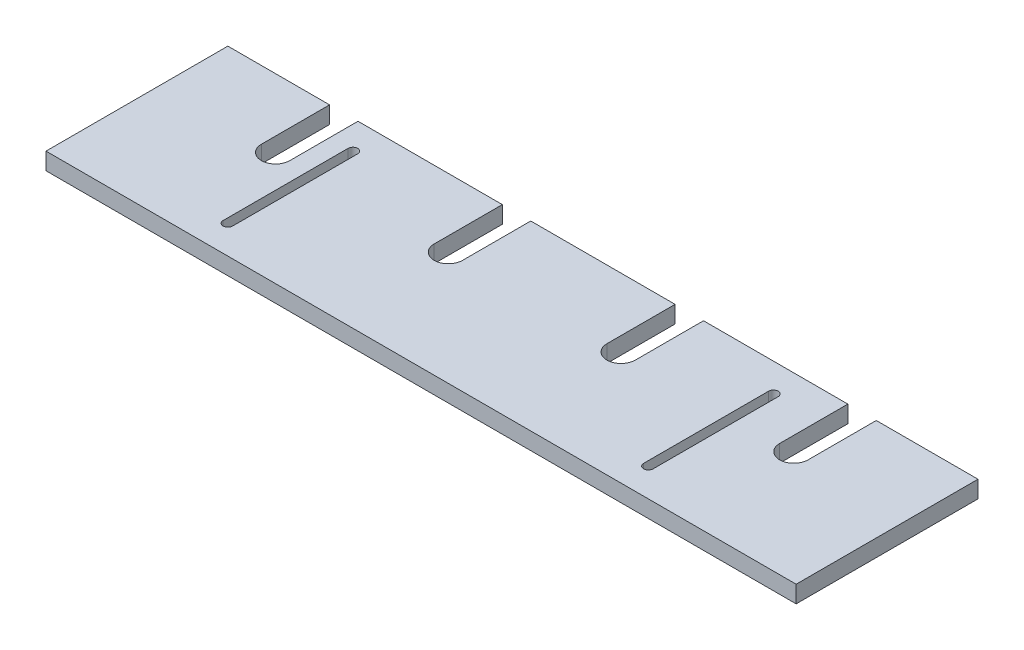
SolidWorks part; units mm, degrees
material "Acrylic (Medium-high impact)"
ref_plane "Front Plane" through (0, 0, 0) normal (0, 0, 1) x (1, 0, 0)
ref_plane "Top Plane" through (0, 0, 0) normal (0, 1, 0) x (1, 0, 0)
ref_plane "Right Plane" through (0, 0, 0) normal (1, 0, 0) x (0, 0, -1)
sketch "Sketch1" plane through (0, 0, 0) normal (0, 1, 0) x (1, 0, 0)
  line L1 (-88.9, -50.8) -> (88.9, -50.8)
  line L2 (-88.9, -50.8) -> (-88.9, 50.8)
  line L3 (-88.9, 50.8) -> (88.9, 50.8)
  line L4 (88.9, -50.8) -> (88.9, 50.8)
  line L5 (-88.9, -50.8) -> (88.9, 50.8) construction
  line L6 (-88.9, 50.8) -> (88.9, -50.8) construction
  line L7 (12.7, -50.8) -> (-190.5, -50.8)
  line L11 (-444.5, -50.8) -> (-292.1, -50.8)
  point P0 (0, 0)
  dimension "D1" = 177.8
  dimension "D2" = 101.6
extrude "Boss-Extrude1" [suppressed] add sketch "Sketch1" along normal mid plane 9.525 contours L1 L4 L3 L2
sketch "Sketch2" [suppressed] plane through (0, 0, 0) normal (0, 1, 0) x (1, 0, 0)
  line L0 (-250.825, -28.575) -> (250.825, -28.575) construction
  line L1 (161.925, -28.575) -> (60.325, -28.575)
  line L2 (161.925, -28.575) -> (161.925, -92.075)
  line L3 (161.925, -92.075) -> (60.325, -92.075)
  line L4 (60.325, -28.575) -> (60.325, -92.075)
  line L5 (0, -5.2388) -> (0, 5.2388) construction
  line L6 (-79.375, -28.575) -> (-168.275, -28.575)
  line L7 (-79.375, -28.575) -> (-79.375, -92.075)
  line L8 (-79.375, -92.075) -> (-168.275, -92.075)
  line L9 (-168.275, -28.575) -> (-168.275, -92.075)
  line L10 (250.825, -28.575) -> (250.825, 28.575) construction
  line L11 (-250.825, -28.575) -> (-250.825, 28.575) construction
  line L12 (-250.825, 28.575) -> (250.825, 28.575) construction
  line L13 (250.825, -28.575) -> (250.825, 28.575) construction
  line L14 (161.925, -28.575) -> (250.825, -28.575)
  line L15 (161.925, -28.575) -> (161.925, -71.755)
  line L16 (161.925, -71.755) -> (250.825, -71.755)
  line L17 (250.825, -28.575) -> (250.825, -71.755)
  line L18 (-250.825, -28.575) -> (-250.825, 28.575) construction
  line L19 (-79.375, -28.575) -> (60.325, -28.575)
  line L20 (-79.375, -28.575) -> (-79.375, -53.975)
  line L21 (-79.375, -53.975) -> (60.325, -53.975)
  line L22 (60.325, -28.575) -> (60.325, -53.975)
  line L23 (-168.275, -28.575) -> (-250.825, -28.575)
  line L24 (-168.275, -28.575) -> (-168.275, -71.755)
  line L25 (-168.275, -71.755) -> (-250.825, -71.755)
  line L26 (-250.825, -28.575) -> (-250.825, -71.755)
  point P19 (60.325, -92.075)
  dimension "D1" = 139.7
  dimension "D2" = 88.9
  dimension "D3" = 82.55
  dimension "D4" = 79.375
  dimension "D5" = 120.65
  dimension "D6" = 43.18
  dimension "D7" = 25.4
  dimension "D8" = 43.18
extrude "Boss-Extrude2" [suppressed] add sketch "Sketch2" along normal mid plane 9.525 contours L6 L9 L8 L7 | L23 L26 L25 L9 | L7 L21 L4 L19 | L17 L14 L2 L16
sketch "Sketch3" [suppressed] plane through (0, 4.7625, 0) normal (0, 1, 0) x (1, 0, 0)
  line L0 (-149.225, 247.65) -> (149.225, 247.65) construction
  line L1 (-98.425, 12.7) -> (98.425, 12.7)
  line L2 (-98.425, 12.7) -> (-98.425, -101.6)
  line L3 (-98.425, -101.6) -> (98.425, -101.6)
  line L4 (98.425, 12.7) -> (98.425, -101.6)
  line L5 (-98.425, 12.7) -> (98.425, -101.6) construction
  line L6 (-98.425, -101.6) -> (98.425, 12.7) construction
  line L7 (-149.225, -247.65) -> (149.225, -247.65) construction
  point P0 (0, -44.45)
  point P7 (0, 247.65)
  point P8 (0, 12.7)
  dimension "D1" = 196.85
  dimension "D2" = 114.3
  dimension "D3" = 203.2
extrude "Cut-Extrude1" [suppressed] cut sketch "Sketch3" against normal through all and the other way through all
sketch "Sketch4" [suppressed] plane through (0, -4.7625, 0) normal (0, -1, 0) x (1, 0, 0)
  line L0 (-107.315, 31.75) -> (107.315, 31.75) construction
  line L1 (-107.315, 33.9979) -> (107.315, 33.9979)
  line L2 (-107.315, 29.5021) -> (107.315, 29.5021)
  line L3 (-107.315, 6.35) -> (107.315, 6.35) construction
  line L4 (-107.315, 8.5979) -> (107.315, 8.5979)
  line L5 (-107.315, 4.1021) -> (107.315, 4.1021)
  arc A0 (-107.315, 33.9979) -> (-107.315, 29.5021) centre (-107.315, 31.75) ccw
  arc A1 (107.315, 29.5021) -> (107.315, 33.9979) centre (107.315, 31.75) ccw
  arc A2 (-107.315, 8.5979) -> (-107.315, 4.1021) centre (-107.315, 6.35) ccw
  arc A3 (107.315, 4.1021) -> (107.315, 8.5979) centre (107.315, 6.35) ccw
  point P0 (-107.315, 31.75)
  point P1 (107.315, 31.75)
  point P3 (107.315, 6.35)
  point P5 (-107.315, 6.35)
  point P10 (0, 31.75)
  point P15 (0, 6.35)
  dimension "D1" = 4.4958
  dimension "D2" = 4.4958
extrude "Cut-Extrude2" [suppressed] cut sketch "Sketch4" against normal through all
sketch "Sketch5" [suppressed] plane through (0, -4.7625, 0) normal (0, -1, 0) x (1, 0, 0)
  line L0 (69.85, 79.375) -> (69.85, -9.525) construction
  line L1 (60.325, 53.975) -> (60.325, 92.075) construction
  line L2 (161.925, 92.075) -> (60.325, 92.075) construction
  line L3 (-247.65, -22.225) -> (247.65, -22.225) construction
  line L4 (69.85, 79.375) -> (69.85, -9.525) construction
  line L5 (72.0979, 79.375) -> (72.0979, -9.525)
  line L6 (67.6021, 79.375) -> (67.6021, -9.525)
  line L7 (-88.9, 79.375) -> (-88.9, -9.525) construction
  line L8 (-79.375, 53.975) -> (-79.375, 92.075) construction
  line L9 (-79.375, 92.075) -> (-168.275, 92.075) construction
  line L10 (-88.9, 79.375) -> (-88.9, -9.525) construction
  line L11 (-86.6521, 79.375) -> (-86.6521, -9.525)
  line L12 (-91.1479, 79.375) -> (-91.1479, -9.525)
  arc A0 (72.0979, 79.375) -> (67.6021, 79.375) centre (69.85, 79.375) ccw
  arc A1 (67.6021, -9.525) -> (72.0979, -9.525) centre (69.85, -9.525) ccw
  arc A2 (-86.6521, 79.375) -> (-91.1479, 79.375) centre (-88.9, 79.375) ccw
  arc A3 (-91.1479, -9.525) -> (-86.6521, -9.525) centre (-88.9, -9.525) ccw
  point P8 (69.85, 34.925)
  point P19 (-88.9, 34.925)
  dimension "D1" = 9.525
  dimension "D2" = 12.7
  dimension "D3" = 12.7
  dimension "D4" = 4.4958
  dimension "D5" = 9.525
  dimension "D6" = 12.7
  dimension "D7" = 12.7
  dimension "D8" = 4.4958
extrude "Cut-Extrude3" [suppressed] cut sketch "Sketch5" against normal through all contours L12 A3 L11 A2 | L6 A1 L5 A0
sketch "Sketch6" [suppressed] plane through (0, 4.7625, 0) normal (0, 1, 0) x (1, 0, 0)
  line L0 (-79.375, -38.1) -> (-79.375, 38.1) construction
  line L1 (-88.9, -50.8) -> (-88.9, 50.8) construction
  line L2 (-88.9, -50.8) -> (88.9, -50.8) construction
  line L3 (-88.9, 50.8) -> (88.9, 50.8) construction
  line L4 (79.375, -38.1) -> (79.375, 38.1) construction
  line L5 (88.9, -50.8) -> (88.9, 50.8) construction
  line L6 (-79.375, -38.1) -> (-79.375, 38.1) construction
  line L7 (-81.6229, -38.1) -> (-81.6229, 38.1)
  line L8 (-77.1271, -38.1) -> (-77.1271, 38.1)
  line L9 (79.375, -38.1) -> (79.375, 38.1) construction
  line L10 (77.1271, -38.1) -> (77.1271, 38.1)
  line L11 (81.6229, -38.1) -> (81.6229, 38.1)
  arc A0 (-81.6229, -38.1) -> (-77.1271, -38.1) centre (-79.375, -38.1) ccw
  arc A1 (-77.1271, 38.1) -> (-81.6229, 38.1) centre (-79.375, 38.1) ccw
  arc A2 (77.1271, -38.1) -> (81.6229, -38.1) centre (79.375, -38.1) ccw
  arc A3 (81.6229, 38.1) -> (77.1271, 38.1) centre (79.375, 38.1) ccw
  point P12 (-79.375, 0)
  point P17 (79.375, 0)
  dimension "D1" = 9.525
  dimension "D2" = 12.7
  dimension "D3" = 12.7
  dimension "D4" = 9.525
  dimension "D5" = 12.7
  dimension "D6" = 12.7
  dimension "D7" = 4.4958
  dimension "D8" = 4.4958
extrude "Cut-Extrude4" [suppressed] cut sketch "Sketch6" against normal through all
sketch "Sketch7" [suppressed] plane through (0, 4.7625, 0) normal (0, 1, 0) x (1, 0, 0)
  point P0 (115.1313, 66.802)
  point P1 (139.827, 42.1063)
  point P3 (-139.827, 42.1063)
  point P5 (-115.1313, 66.802)
hole_wizard "#12 Clearance Hole1" [suppressed] positions "Sketch8" profile "Sketch9" hole size "#12" standard "ANSI Inch"
sketch "Sketch8" [suppressed] plane through (0, 4.7625, 0) normal (0, 1, 0) x (1, 0, 0)
  point P0 (-139.827, 42.1063)
  point P3 (-115.1313, 66.802)
  point P6 (115.1313, 66.802)
  point P9 (139.827, 42.1063)
sketch "Sketch9" plane through (-139.827, 4.7625, -42.1063) normal (1, 0, 0) x (0, 0, 1)
  line L0 (0, 0) -> (0, 18.1964)
  line L1 (0, 18.1964) -> (2.8067, 16.51)
  line L2 (2.8067, 16.51) -> (2.8067, 0)
  line L5 (2.8067, 0) -> (0, 0)
  line L10 (0, 18.1964) -> (-2.8067, 16.51) construction
  line L11 (0, -6.35) -> (0, 107.95) construction
  dimension "Hole Dia." = 5.6134
  dimension "Hole Depth" = 16.51
  dimension "Drill Angle" = 118
sketch "Sketch10" [suppressed] plane through (0, -4.7625, 0) normal (0, -1, 0) x (1, 0, 0)
  point P0 (223.8375, -6.35)
  point P1 (223.8375, 19.05)
  point P3 (-223.8375, 19.05)
  point P5 (-223.8375, -6.35)
hole_wizard "#12 Clearance Hole3" [suppressed] positions "Sketch11" profile "Sketch12" hole size "#12" standard "ANSI Inch"
sketch "Sketch11" [suppressed] plane through (0, -4.7625, 0) normal (0, -1, 0) x (-1, 0, 0)
  point P0 (-223.8375, -19.05)
  point P3 (-223.8375, 6.35)
  point P6 (223.8375, -19.05)
  point P9 (223.8375, 6.35)
sketch "Sketch12" plane through (223.8375, -4.7625, 19.05) normal (1, 0, 0) x (0, 0, -1)
  line L0 (0, 0) -> (0, 18.1964)
  line L1 (0, 18.1964) -> (2.8067, 16.51)
  line L2 (2.8067, 16.51) -> (2.8067, 0)
  line L5 (2.8067, 0) -> (0, 0)
  line L10 (0, 18.1964) -> (-2.8067, 16.51) construction
  line L11 (0, -6.35) -> (0, 107.95) construction
  dimension "Hole Dia." = 5.6134
  dimension "Hole Depth" = 16.51
  dimension "Drill Angle" = 118
sketch "Sketch13" [suppressed] plane through (0, -4.7625, 0) normal (0, -1, 0) x (1, 0, 0)
  point P0 (133.35, -223.8375)
  point P1 (107.95, -223.8375)
  point P3 (-107.95, -223.8375)
  point P5 (-133.35, -223.8375)
  point P7 (133.35, 223.8375)
  point P9 (107.95, 223.8375)
  point P11 (-107.95, 223.8375)
  point P13 (-133.35, 223.8375)
hole_wizard "#12 Clearance Hole2" [suppressed] positions "Sketch14" profile "Sketch15" hole size "#12" standard "ANSI Inch"
sketch "Sketch14" [suppressed] plane through (0, -4.7625, 0) normal (0, -1, 0) x (-1, 0, 0)
  point P0 (107.95, -223.8375)
  point P3 (133.35, -223.8375)
  point P6 (133.35, 223.8375)
  point P9 (107.95, 223.8375)
  point P12 (-133.35, 223.8375)
  point P15 (-107.95, 223.8375)
  point P18 (-133.35, -223.8375)
  point P21 (-107.95, -223.8375)
sketch "Sketch15" plane through (-107.95, -4.7625, 223.8375) normal (1, 0, 0) x (0, 0, -1)
  line L0 (0, 0) -> (0, 18.1964)
  line L1 (0, 18.1964) -> (2.8067, 16.51)
  line L2 (2.8067, 16.51) -> (2.8067, 0)
  line L5 (2.8067, 0) -> (0, 0)
  line L10 (0, 18.1964) -> (-2.8067, 16.51) construction
  line L11 (0, -6.35) -> (0, 107.95) construction
  dimension "Hole Dia." = 5.6134
  dimension "Hole Depth" = 16.51
  dimension "Drill Angle" = 118
sketch "Sketch16" [suppressed] plane through (0, 4.7625, 0) normal (0, 1, 0) x (1, 0, 0)
  line L0 (88.9, -50.8) -> (88.9, 50.8) construction
  line L1 (-88.9, -50.8) -> (-88.9, 50.8) construction
  line L2 (-88.9, -50.8) -> (88.9, -50.8) construction
  point P0 (79.375, -38.1)
  point P1 (-79.375, -38.1)
  dimension "D1" = 9.525
  dimension "D2" = 9.525
  dimension "D3" = 12.7
hole_wizard "#8 Clearance Hole1" [suppressed] positions "Sketch17" profile "Sketch19" hole size "#8" standard "ANSI Inch"
sketch "Sketch17" [suppressed] plane through (0, 4.7625, 0) normal (0, 1, 0) x (1, 0, 0)
  point P0 (79.375, -38.1)
  point P3 (-79.375, -38.1)
sketch "Sketch19" plane through (79.375, 4.7625, 38.1) normal (1, 0, 0) x (0, 0, 1)
  line L0 (0, 0) -> (0, 12.0187)
  line L1 (0, 12.0187) -> (2.2479, 10.668)
  line L2 (2.2479, 10.668) -> (2.2479, 0)
  line L5 (2.2479, 0) -> (0, 0)
  line L10 (0, 12.0187) -> (-2.2479, 10.668) construction
  line L11 (0, -6.35) -> (0, 107.95) construction
  dimension "Hole Dia." = 4.4958
  dimension "Hole Depth" = 10.668
  dimension "Drill Angle" = 118
sketch "Sketch20" [suppressed] plane through (0, -4.7625, 0) normal (0, -1, 0) x (1, 0, 0)
  line L0 (-149.225, 247.65) -> (149.225, 247.65) construction
  line L1 (23.9395, 147.5105) -> (-23.9395, 147.5105)
  line L2 (23.9395, 147.5105) -> (23.9395, 195.3895)
  line L3 (23.9395, 195.3895) -> (-23.9395, 195.3895)
  line L4 (-23.9395, 147.5105) -> (-23.9395, 195.3895)
  line L5 (23.9395, 147.5105) -> (-23.9395, 195.3895) construction
  line L6 (23.9395, 195.3895) -> (-23.9395, 147.5105) construction
  line L8 (38.1, 155.575) -> (-38.1, 155.575) construction
  line L9 (38.1, 155.575) -> (38.1, 187.325) construction
  line L10 (38.1, 187.325) -> (-38.1, 187.325) construction
  line L11 (-38.1, 155.575) -> (-38.1, 187.325) construction
  point P0 (0, 171.45)
  point P7 (0, 247.65)
  point P8 (38.1, 155.575)
  point P9 (38.1, 187.325)
  point P10 (-38.1, 155.575)
  point P11 (-38.1, 187.325)
  point P18 (0, 187.325)
  point P19 (0, 195.3895)
  point P20 (-38.1, 171.45)
  point P21 (-23.9395, 171.45)
  dimension "D1" = 47.879
  dimension "D2" = 47.879
  dimension "D3" = 38.1
  dimension "D4" = 15.875
  dimension "D5" = 76.2
extrude "Cut-Extrude5" [suppressed] cut sketch "Sketch20" against normal through all contours L1 L4 L3 L2
hole_wizard "#10 Clearance Hole1" [suppressed] positions "Sketch21" profile "Sketch22" hole size "#10" standard "ANSI Inch"
sketch "Sketch21" [suppressed] plane through (0, -4.7625, 0) normal (0, -1, 0) x (-1, 0, 0)
  point P0 (-38.1, -155.575)
  point P3 (38.1, -155.575)
  point P6 (38.1, -187.325)
  point P9 (-38.1, -187.325)
sketch "Sketch22" plane through (38.1, -4.7625, 155.575) normal (1, 0, 0) x (0, 0, -1)
  line L0 (0, 0) -> (0, 12.2018)
  line L1 (0, 12.2018) -> (2.5527, 10.668)
  line L2 (2.5527, 10.668) -> (2.5527, 0)
  line L5 (2.5527, 0) -> (0, 0)
  line L10 (0, 12.2018) -> (-2.5527, 10.668) construction
  line L11 (0, -6.35) -> (0, 107.95) construction
  dimension "Hole Dia." = 5.1054
  dimension "Hole Depth" = 10.668
  dimension "Drill Angle" = 118
sketch "Sketch23" [suppressed] plane through (-250.825, 0, 0) normal (-1, 0, 0) x (0, 0, 1)
  line L4 (-28.575, -4.7625) -> (71.755, -4.7625)
  line L5 (71.755, -4.7625) -> (71.755, 4.7625)
  line L6 (71.755, 4.7625) -> (-28.575, 4.7625)
  line L7 (-28.575, 4.7625) -> (-28.575, -4.7625)
  line L8 (-28.575, -4.7625) -> (71.755, -4.7625)
  line L9 (71.755, -4.7625) -> (71.755, 4.7625)
  line L10 (71.755, 4.7625) -> (-28.575, 4.7625)
  line L11 (-28.575, 4.7625) -> (-28.575, -4.7625)
  dimension "D1" = 0
extrude "Boss-Extrude3" [suppressed] add sketch "Sketch23" along normal blind 6.35
mirror "Mirror1" [suppressed] about plane through (0, 0, 0) normal (1, 0, 0)
sketch "Sketch27" [suppressed] plane through (0, 4.7625, 0) normal (0, 1, 0) x (1, 0, 0)
  line L1 (257.175, -71.755) -> (257.175, 28.575) construction
  line L2 (-257.175, 28.575) -> (257.175, 28.575) construction
  point P0 (241.3, 12.7)
  dimension "D1" = 15.875
  dimension "D2" = 15.875
hole_wizard "#10 Clearance Hole2" [suppressed] positions "Sketch28" profile "Sketch30" hole size "#10" standard "ANSI Inch"
sketch "Sketch28" [suppressed] plane through (0, 4.7625, 0) normal (0, 1, 0) x (1, 0, 0)
  point P0 (241.3, 12.7)
sketch "Sketch30" plane through (241.3, 4.7625, -12.7) normal (1, 0, 0) x (0, 0, 1)
  line L0 (0, 0) -> (0, 9.525)
  line L1 (0, 9.525) -> (2.5527, 9.525)
  line L2 (2.5527, 9.525) -> (2.5527, 0)
  line L5 (2.5527, 0) -> (0, 0)
  line L11 (0, -6.35) -> (0, 107.95) construction
  dimension "Thru Hole Dia." = 5.1054
  dimension "Thru Hole Depth" = 9.525
pattern_linear "LPattern1" [suppressed] count 6 spacing 96.52
sketch "Sketch31" [suppressed] plane through (0, 4.7625, 0) normal (0, 1, 0) x (1, 0, 0)
  line L1 (0, -5.2388) -> (0, 5.2388) construction
  line L2 (-149.225, 76.2) -> (149.225, 76.2) construction
  point P0 (-95.25, 60.325)
  dimension "D1" = 15.875
  dimension "D2" = 95.25
hole_wizard "#10 Clearance Hole3" [suppressed] positions "Sketch32" profile "Sketch33" hole size "#10" standard "ANSI Inch"
sketch "Sketch32" [suppressed] plane through (0, 4.7625, 0) normal (0, 1, 0) x (1, 0, 0)
  point P0 (-95.25, 60.325)
sketch "Sketch33" plane through (-95.25, 4.7625, -60.325) normal (1, 0, 0) x (0, 0, 1)
  line L0 (0, 0) -> (0, 9.525)
  line L1 (0, 9.525) -> (2.5527, 9.525)
  line L2 (2.5527, 9.525) -> (2.5527, 0)
  line L5 (2.5527, 0) -> (0, 0)
  line L11 (0, -6.35) -> (0, 107.95) construction
  dimension "Thru Hole Dia." = 5.1054
  dimension "Thru Hole Depth" = 9.525
pattern_linear "LPattern2" [suppressed] count 4 spacing 63.5
sketch "Sketch34" [suppressed] plane through (0, 4.7625, 0) normal (0, 1, 0) x (1, 0, 0)
  line L0 (0, -5.2388) -> (0, 5.2388) construction
  line L1 (-149.225, 247.65) -> (149.225, 247.65) construction
  point P0 (-63.5, 241.3)
  dimension "D1" = 63.5
  dimension "D2" = 6.35
hole_wizard "#10 Clearance Hole4" [suppressed] positions "Sketch35" profile "Sketch36" hole size "#10" standard "ANSI Inch"
sketch "Sketch35" [suppressed] plane through (0, 4.7625, 0) normal (0, 1, 0) x (1, 0, 0)
  point P0 (-63.5, 241.3)
sketch "Sketch36" plane through (-63.5, 4.7625, -241.3) normal (1, 0, 0) x (0, 0, 1)
  line L0 (0, 0) -> (0, 9.525)
  line L1 (0, 9.525) -> (2.5527, 9.525)
  line L2 (2.5527, 9.525) -> (2.5527, 0)
  line L5 (2.5527, 0) -> (0, 0)
  line L11 (0, -6.35) -> (0, 107.95) construction
  dimension "Thru Hole Dia." = 5.1054
  dimension "Thru Hole Depth" = 9.525
pattern_linear "LPattern3" [suppressed] count 3 spacing 63.5
mirror "Mirror2" [suppressed] about plane through (0, 0, 0) normal (0, 0, 1)
sketch "Sketch37" [suppressed] plane through (0, 4.7625, 0) normal (0, 1, 0) x (1, 0, 0)
  line L0 (-5.2388, 0) -> (5.2388, 0) construction
  line L1 (-149.225, -247.65) -> (-149.225, 247.65) construction
  point P0 (-142.875, 0)
  dimension "D1" = 6.35
hole_wizard "#10 Clearance Hole5" [suppressed] positions "Sketch38" profile "Sketch39" hole size "#10" standard "ANSI Inch"
sketch "Sketch38" [suppressed] plane through (0, 4.7625, 0) normal (0, 1, 0) x (1, 0, 0)
  point P0 (-142.875, 0)
sketch "Sketch39" plane through (-142.875, 4.7625, 0) normal (1, 0, 0) x (0, 0, 1)
  line L0 (0, 0) -> (0, 9.525)
  line L1 (0, 9.525) -> (2.5527, 9.525)
  line L2 (2.5527, 9.525) -> (2.5527, 0)
  line L5 (2.5527, 0) -> (0, 0)
  line L11 (0, -6.35) -> (0, 107.95) construction
  dimension "Thru Hole Dia." = 5.1054
  dimension "Thru Hole Depth" = 9.525
pattern_linear "LPattern4" [suppressed] count 3 spacing 96.52 count 3 spacing 96.52
mirror "Mirror3" [suppressed] about plane through (0, 0, 0) normal (1, 0, 0)
sketch "Sketch40" [suppressed] plane through (0, 4.7625, 0) normal (0, 1, 0) x (1, 0, 0)
  line L0 (-79.375, -53.975) -> (-79.375, -92.075) construction
  line L3 (-88.9, -79.375) -> (-88.9, -9.525) construction
  line L4 (-91.1479, -79.375) -> (-91.1479, -9.525)
  line L5 (-86.6521, -79.375) -> (-86.6521, -9.525)
  line L6 (69.85, -79.375) -> (69.85, -9.525) construction
  line L7 (67.6021, -79.375) -> (67.6021, -9.525)
  line L8 (72.0979, -79.375) -> (72.0979, -9.525)
  line L9 (60.325, -53.975) -> (60.325, -92.075) construction
  line L12 (-79.375, -92.075) -> (-168.275, -92.075) construction
  line L13 (161.925, -92.075) -> (60.325, -92.075) construction
  arc A2 (-91.1479, -79.375) -> (-86.6521, -79.375) centre (-88.9, -79.375) ccw
  arc A3 (-86.6521, -9.525) -> (-91.1479, -9.525) centre (-88.9, -9.525) ccw
  arc A4 (67.6021, -79.375) -> (72.0979, -79.375) centre (69.85, -79.375) ccw
  arc A5 (72.0979, -9.525) -> (67.6021, -9.525) centre (69.85, -9.525) ccw
  point P7 (-88.9, -44.45)
  point P14 (69.85, -44.45)
  dimension "D1" = 9.525
  dimension "D2" = 4.4958
  dimension "D3" = 4.4958
  dimension "D4" = 9.525
  dimension "D5" = 12.7
  dimension "D6" = 12.7
  dimension "D7" = 69.85
  dimension "D8" = 69.85
extrude "Cut-Extrude6" [suppressed] cut sketch "Sketch40" against normal up to next
sketch "Sketch41" [suppressed] plane through (0, -4.7625, 0) normal (0, -1, 0) x (1, 0, 0)
  point P0 (120.65, -32.5755)
  point P1 (-120.65, -32.5755)
  point P3 (-120.65, 121.4755)
  point P5 (120.65, 121.4755)
hole_wizard "#10 Clearance Hole6" [suppressed] positions "Sketch42" profile "Sketch43" hole size "#10" standard "ANSI Inch"
sketch "Sketch42" [suppressed] plane through (0, 4.7625, 0) normal (0, 1, 0) x (1, 0, 0)
  point P0 (120.65, 32.5755)
  point P3 (120.65, -121.4755)
  point P6 (-120.65, -121.4755)
  point P9 (-120.65, 32.5755)
sketch "Sketch43" plane through (120.65, 4.7625, -32.5755) normal (1, 0, 0) x (0, 0, 1)
  line L0 (0, 0) -> (0, 9.525)
  line L1 (0, 9.525) -> (2.5527, 9.525)
  line L2 (2.5527, 9.525) -> (2.5527, 0)
  line L5 (2.5527, 0) -> (0, 0)
  line L11 (0, -6.35) -> (0, 107.95) construction
  dimension "Thru Hole Dia." = 5.1054
  dimension "Thru Hole Depth" = 9.525
sketch "Sketch44" [suppressed] plane through (0, 4.7625, 0) normal (0, 1, 0) x (1, 0, 0)
  line L0 (0, -5.2388) -> (0, 5.2388) construction
  line L2 (120.65, 32.5755) -> (-120.65, 32.5755) construction
  line L3 (120.65, -121.4755) -> (-120.65, -121.4755) construction
  point P0 (76.2, 32.5755)
  point P1 (0, 32.5755)
  point P2 (-76.2, 32.5755)
  point P3 (76.2, -121.4755)
  point P4 (0, -121.4755)
  point P5 (-76.2, -121.4755)
  dimension "D1" = 76.2
  dimension "D2" = 76.2
hole_wizard "#10 Clearance Hole7" [suppressed] positions "Sketch45" profile "Sketch46" hole size "#10" standard "ANSI Inch"
sketch "Sketch45" [suppressed] plane through (0, 4.7625, 0) normal (0, 1, 0) x (1, 0, 0)
  point P0 (76.2, 32.5755)
  point P3 (0, 32.5755)
  point P6 (-76.2, 32.5755)
  point P9 (76.2, -121.4755)
  point P12 (0, -121.4755)
  point P15 (-76.2, -121.4755)
sketch "Sketch46" plane through (76.2, 4.7625, -32.5755) normal (1, 0, 0) x (0, 0, 1)
  line L0 (0, 0) -> (0, 9.525)
  line L1 (0, 9.525) -> (2.5527, 9.525)
  line L2 (2.5527, 9.525) -> (2.5527, 0)
  line L5 (2.5527, 0) -> (0, 0)
  line L11 (0, -6.35) -> (0, 107.95) construction
  dimension "Thru Hole Dia." = 5.1054
  dimension "Thru Hole Depth" = 9.525
sketch "Sketch47" [suppressed] plane through (0, 4.7625, 0) normal (0, 1, 0) x (1, 0, 0)
  line L1 (-142.875, 0) -> (-142.875, -96.52) construction
  line L2 (142.875, 0) -> (142.875, -96.52) construction
  point P0 (-142.875, -71.12)
  point P1 (142.875, -25.4)
  point P2 (-142.875, -25.4)
  point P3 (142.875, -71.12)
  dimension "D1" = 25.4
  dimension "D2" = 25.4
  dimension "D3" = 25.4
  dimension "D4" = 25.4
hole_wizard "#10 Clearance Hole8" [suppressed] positions "Sketch48" profile "Sketch49" hole size "#10" standard "ANSI Inch"
sketch "Sketch48" [suppressed] plane through (0, 4.7625, 0) normal (0, 1, 0) x (1, 0, 0)
  point P0 (-142.875, -71.12)
  point P3 (142.875, -25.4)
  point P7 (-142.875, -25.4)
  point P10 (142.875, -71.12)
sketch "Sketch49" plane through (-142.875, 4.7625, 71.12) normal (1, 0, 0) x (0, 0, 1)
  line L0 (0, 0) -> (0, 9.525)
  line L1 (0, 9.525) -> (2.5527, 9.525)
  line L2 (2.5527, 9.525) -> (2.5527, 0)
  line L5 (2.5527, 0) -> (0, 0)
  line L11 (0, -6.35) -> (0, 107.95) construction
  dimension "Thru Hole Dia." = 5.1054
  dimension "Thru Hole Depth" = 9.525
sketch "Sketch50" plane through (0, 0, 0) normal (0, 1, 0) x (1, 0, 0)
  line L1 (-209.55, -50.8) -> (209.55, -50.8)
  line L2 (-209.55, -50.8) -> (-209.55, 50.8)
  line L3 (-209.55, 50.8) -> (209.55, 50.8)
  line L4 (209.55, -50.8) -> (209.55, 50.8)
  line L5 (-209.55, -50.8) -> (209.55, 50.8) construction
  line L6 (-209.55, 50.8) -> (209.55, -50.8) construction
  point P0 (0, 0)
  dimension "D1" = 419.1
  dimension "D2" = 101.6
extrude "Boss-Extrude4" add sketch "Sketch50" along normal blind 9.525
sketch "Sketch51" plane through (0, 0, 0) normal (0, -1, 0) x (1, 0, 0)
  line L0 (144.78, -12.7) -> (144.78, -50.8) construction
  line L1 (152.7175, -12.7) -> (152.7175, -50.8)
  line L2 (136.8425, -12.7) -> (136.8425, -50.8)
  line L3 (209.55, -50.8) -> (-209.55, -50.8) construction
  line L4 (209.55, 50.8) -> (209.55, -50.8) construction
  line L5 (48.26, -50.8) -> (48.26, -12.7) construction
  line L7 (40.3225, -50.8) -> (40.3225, -12.7)
  line L8 (56.1975, -50.8) -> (56.1975, -12.7)
  arc A0 (152.7175, -12.7) -> (136.8425, -12.7) centre (144.78, -12.7) ccw
  arc A1 (136.8425, -50.8) -> (152.7175, -50.8) centre (144.78, -50.8) ccw
  arc A2 (40.3225, -50.8) -> (56.1975, -50.8) centre (48.26, -50.8) ccw
  arc A3 (56.1975, -12.7) -> (40.3225, -12.7) centre (48.26, -12.7) ccw
  point P2 (144.78, -31.75)
  point P7 (48.26, -31.75)
  dimension "D1" = 38.1
  dimension "D2" = 64.77
  dimension "D3" = 15.875
  dimension "D4" = 15.875
  dimension "D5" = 96.52
extrude "Cut-Extrude7" cut sketch "Sketch51" against normal up to next
mirror "Mirror4" about plane through (0, 0, 0) normal (1, 0, 0) of "Cut-Extrude7"
sketch "Sketch52" [suppressed] plane through (0, 4.7625, 0) normal (0, 1, 0) x (1, 0, 0)
  line L0 (-79.375, -92.075) -> (-168.275, -92.075) construction
  line L1 (161.925, -92.075) -> (60.325, -92.075) construction
  point P0 (-123.825, -38.1)
  point P1 (111.125, -38.1)
  point P4 (-123.825, -92.075)
  point P7 (111.125, -92.075)
  dimension "D1" = 53.975
hole_wizard "#10 Clearance Hole9" [suppressed] positions "Sketch53" profile "Sketch54" hole size "#10" standard "ANSI Inch"
sketch "Sketch53" plane through (0, 4.7625, 0) normal (0, 1, 0) x (1, 0, 0)
  point P0 (-123.825, -38.1)
  point P3 (111.125, -38.1)
sketch "Sketch54" plane through (-123.825, 4.7625, 38.1) normal (1, 0, 0) x (0, 0, 1)
  line L0 (0, 0) -> (0, 9.525)
  line L1 (0, 9.525) -> (2.5527, 9.525)
  line L2 (2.5527, 9.525) -> (2.5527, 0)
  line L5 (2.5527, 0) -> (0, 0)
  line L11 (0, -6.35) -> (0, 107.95) construction
  dimension "Thru Hole Dia." = 5.1054
  dimension "Thru Hole Depth" = 9.525
sketch "Sketch55" plane through (0, 0, 0) normal (0, -1, 0) x (1, 0, 0)
  line L0 (111.125, 34.925) -> (111.125, -34.925) construction
  line L1 (113.792, 34.925) -> (113.792, -34.925)
  line L2 (108.458, 34.925) -> (108.458, -34.925)
  line L3 (-123.825, 34.925) -> (-123.825, -34.925) construction
  line L4 (209.55, 50.8) -> (209.55, -50.8) construction
  line L5 (-121.158, 34.925) -> (-121.158, -34.925)
  line L6 (-126.492, 34.925) -> (-126.492, -34.925)
  line L7 (-209.55, -50.8) -> (-209.55, 50.8) construction
  arc A0 (113.792, 34.925) -> (108.458, 34.925) centre (111.125, 34.925) ccw
  arc A1 (108.458, -34.925) -> (113.792, -34.925) centre (111.125, -34.925) ccw
  arc A2 (-121.158, 34.925) -> (-126.492, 34.925) centre (-123.825, 34.925) ccw
  arc A3 (-126.492, -34.925) -> (-121.158, -34.925) centre (-123.825, -34.925) ccw
  point P2 (111.125, 0)
  point P11 (209.55, 0)
  point P12 (-123.825, 0)
  dimension "D1" = 5.334
  dimension "D2" = 69.85
  dimension "D3" = 98.425
  dimension "D4" = 85.725
  dimension "D5" = 5.334
  dimension "D6" = 69.85
extrude "Cut-Extrude8" cut sketch "Sketch55" against normal up to next contours L6 A3 L5 A2 | L2 A1 L1 A0
sketch "Sketch56" [suppressed] plane through (0, 4.7625, 0) normal (0, 1, 0) x (1, 0, 0)
  line L0 (-257.175, -71.755) -> (-257.175, 28.575) construction
  line L1 (-168.275, -71.755) -> (-257.175, -71.755) construction
  line L2 (257.175, -71.755) -> (257.175, 28.575) construction
  line L3 (161.925, -71.755) -> (257.175, -71.755) construction
  point P0 (-234.95, -62.23)
  point P5 (234.95, -62.23)
  dimension "D1" = 22.225
  dimension "D2" = 9.525
  dimension "D3" = 22.225
  dimension "D4" = 9.525
hole_wizard "#10-32 Tapped Hole2" [suppressed] positions "Sketch57" profile "Sketch58" tap size "#10-32" standard "ANSI Inch"
sketch "Sketch57" plane through (0, 4.7625, 0) normal (0, 1, 0) x (1, 0, 0)
  point P0 (234.95, -62.23)
  point P3 (-234.95, -62.23)
sketch "Sketch58" plane through (234.95, 4.7625, 62.23) normal (1, 0, 0) x (0, 0, 1)
  line L0 (0, 0) -> (0, 9.525)
  line L1 (0, 9.525) -> (2.0193, 9.525)
  line L2 (2.0193, 9.525) -> (2.0193, 0)
  line L5 (2.0193, 0) -> (0, 0)
  line L11 (0, -6.35) -> (0, 107.95) construction
  dimension "Thru Tap Drill Dia." = 4.0386
  dimension "Thru Tap Drill Depth" = 9.525
sketch "Sketch59" [suppressed] plane through (0, 4.7625, 0) normal (0, 1, 0) x (1, 0, 0)
  line L0 (-149.225, -76.2) -> (149.225, -76.2) construction
  line L1 (149.225, -76.2) -> (149.225, 76.2) construction
  line L2 (-149.225, -76.2) -> (-149.225, 76.2) construction
  point P0 (139.7, -14.605)
  point P1 (-139.7, -14.605)
  dimension "D1" = 61.595
  dimension "D2" = 9.525
  dimension "D3" = 9.525
hole_wizard "#10-32 Tapped Hole1" [suppressed] positions "Sketch60" profile "Sketch62" tap size "#10-32" standard "ANSI Inch"
sketch "Sketch60" plane through (0, 4.7625, 0) normal (0, 1, 0) x (1, 0, 0)
  point P0 (-139.7, -14.605)
  point P3 (139.7, -14.605)
sketch "Sketch62" plane through (-139.7, 4.7625, 14.605) normal (1, 0, 0) x (0, 0, 1)
  line L0 (0, 0) -> (0, 9.525)
  line L1 (0, 9.525) -> (2.0193, 9.525)
  line L2 (2.0193, 9.525) -> (2.0193, 0)
  line L5 (2.0193, 0) -> (0, 0)
  line L11 (0, -6.35) -> (0, 107.95) construction
  dimension "Thru Tap Drill Dia." = 4.0386
  dimension "Thru Tap Drill Depth" = 9.525
cosmetic thread "Hole Thread1" [suppressed] parameters "D2"=4.826
cosmetic thread "Hole Thread2" [suppressed] parameters "D2"=4.826
sketch "Sketch63" [suppressed] plane through (0, 4.7625, 0) normal (0, 1, 0) x (1, 0, 0)
  line L0 (-149.225, 76.2) -> (149.225, 76.2) construction
  line L1 (-149.225, -76.2) -> (-149.225, 76.2) construction
  point P0 (-65.0875, 19.05)
  point P1 (-26.9875, 19.05)
  dimension "D1" = 38.1
  dimension "D2" = 57.15
  dimension "D3" = 84.1375
hole_wizard "1/4 Clearance Hole1" [suppressed] positions "Sketch64" profile "Sketch65" hole size "1/4" standard "ANSI Inch"
sketch "Sketch64" plane through (0, 4.7625, 0) normal (0, 1, 0) x (1, 0, 0)
  point P0 (-65.0875, 19.05)
  point P3 (-26.9875, 19.05)
sketch "Sketch65" plane through (-65.0875, 4.7625, -19.05) normal (1, 0, 0) x (0, 0, 1)
  line L0 (0, 0) -> (0, 9.525)
  line L1 (0, 9.525) -> (3.3782, 9.525)
  line L2 (3.3782, 9.525) -> (3.3782, 0)
  line L5 (3.3782, 0) -> (0, 0)
  line L11 (0, -6.35) -> (0, 107.95) construction
  dimension "Thru Hole Dia." = 6.7564
  dimension "Thru Hole Depth" = 9.525
mirror "Mirror5" [suppressed] about plane through (0, 0, 0) normal (1, 0, 0)
sketch "Sketch66" [suppressed] plane through (0, 4.7625, 0) normal (0, 1, 0) x (1, 0, 0)
  line L0 (-128.905, -44.45) -> (128.905, -44.45) construction
  line L1 (98.425, -101.6) -> (98.425, 12.7) construction
  line L2 (149.225, -247.65) -> (149.225, 247.65) construction
  line L3 (0, -5.2388) -> (0, 5.2388) construction
  point P4 (98.425, -44.45)
  point P7 (0, -44.45)
  dimension "D1" = 20.32
hole_wizard "1/4-20 Tapped Hole1" [suppressed] positions "Sketch67" profile "Sketch68" tap size "1/4-20" standard "ANSI Inch"
sketch "Sketch67" plane through (0, 4.7625, 0) normal (0, 1, 0) x (1, 0, 0)
  point P0 (-128.905, -44.45)
  point P3 (128.905, -44.45)
sketch "Sketch68" plane through (-128.905, 4.7625, 44.45) normal (1, 0, 0) x (0, 0, 1)
  line L0 (0, 0) -> (0, 9.525)
  line L1 (0, 9.525) -> (2.5527, 9.525)
  line L2 (2.5527, 9.525) -> (2.5527, 0)
  line L5 (2.5527, 0) -> (0, 0)
  line L11 (0, -6.35) -> (0, 107.95) construction
  dimension "Thru Tap Drill Dia." = 5.1054
  dimension "Thru Tap Drill Depth" = 9.525
